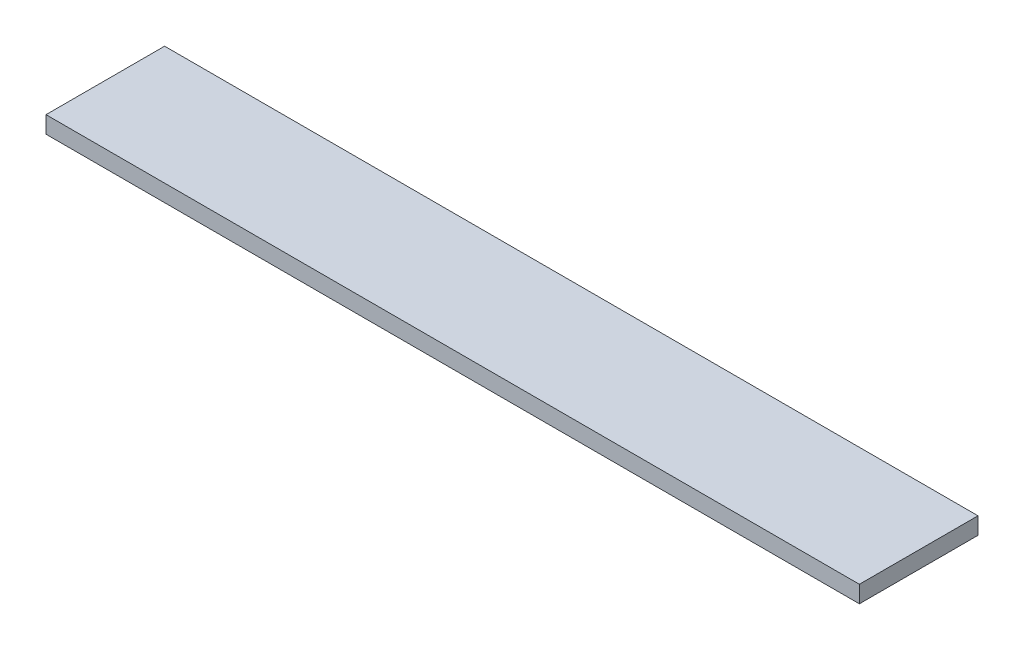
SolidWorks part; units mm, degrees
ref_plane "Front Plane" through (0, 0, 0) normal (0, 0, 1) x (1, 0, 0)
ref_plane "Top Plane" through (0, 0, 0) normal (0, 1, 0) x (1, 0, 0)
ref_plane "Right Plane" through (0, 0, 0) normal (1, 0, 0) x (0, 0, -1)
sketch "Sketch1" plane through (0, 0, 0) normal (0, 1, 0) x (1, 0, 0)
  line L0 (-292.1, -88.9) -> (292.1, -88.9) construction
  line L1 (304.8, -88.9) -> (-304.8, -88.9)
  line L2 (304.8, -88.9) -> (304.8, 0)
  line L3 (304.8, 0) -> (-304.8, 0)
  line L4 (-304.8, -88.9) -> (-304.8, 0)
  line L5 (304.8, -88.9) -> (-304.8, 0) construction
  line L6 (304.8, 0) -> (-304.8, -88.9) construction
  line L7 (304.8, -88.9) -> (304.8, 0) construction
  point P0 (0, -44.45)
extrude "Boss-Extrude1" add sketch "Sketch1" along normal blind 12.7
